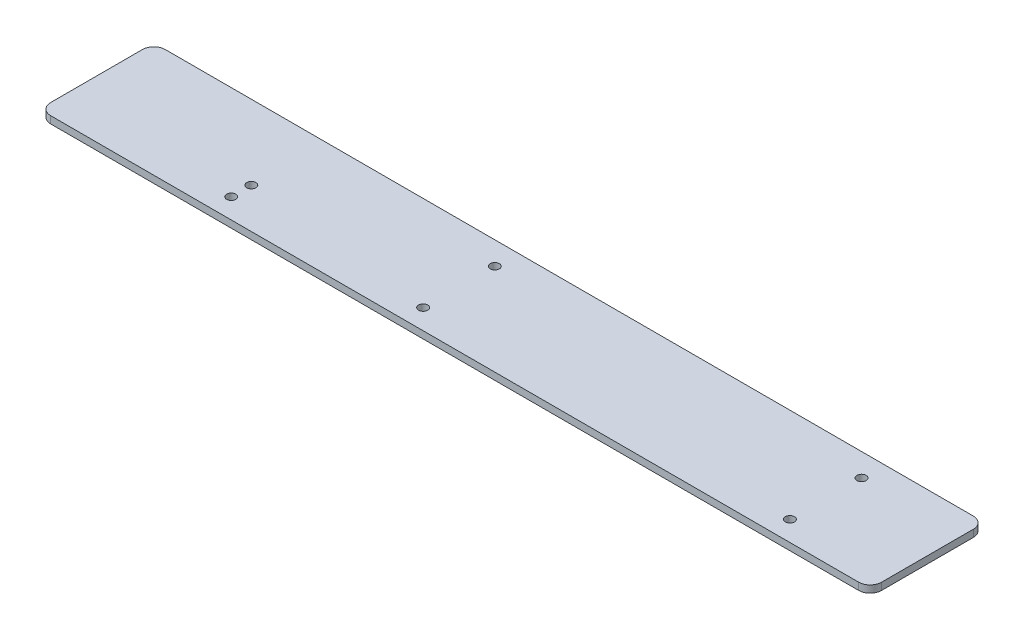
SolidWorks part; units mm, degrees
ref_plane "Front Plane" through (0, 0, 0) normal (0, 0, 1) x (1, 0, 0)
ref_plane "Top Plane" through (0, 0, 0) normal (0, 1, 0) x (1, 0, 0)
ref_plane "Right Plane" through (0, 0, 0) normal (1, 0, 0) x (0, 0, -1)
sketch "Sketch1" plane through (0, 0, 0) normal (0, 1, 0) x (1, 0, 0)
  line L0 (-184.15, -16.51) -> (184.15, -16.51) construction
  line L1 (-184.15, 25.4) -> (184.15, 25.4)
  line L2 (-184.15, 25.4) -> (-184.15, -25.4)
  line L3 (-184.15, -25.4) -> (184.15, -25.4)
  line L4 (184.15, 25.4) -> (184.15, -25.4)
  line L5 (-184.15, 25.4) -> (184.15, -25.4) construction
  line L6 (-184.15, -25.4) -> (184.15, 25.4) construction
  line L7 (-22.86, -16.51) -> (-22.86, 15.24) construction
  line L8 (139.7, -16.51) -> (139.7, 15.24) construction
  line L9 (-107.95, -16.51) -> (-107.95, -7.62) construction
  circle A0 centre (139.7, 15.24) radius 2.032
  circle A1 centre (139.7, -16.51) radius 2.032
  circle A2 centre (-22.86, 15.24) radius 2.032
  circle A3 centre (-22.86, -16.51) radius 2.032
  circle A4 centre (-107.95, -16.51) radius 2.032
  circle A5 centre (-107.95, -7.62) radius 2.032
  point P0 (0, 0)
  dimension "D4" = 4.064
  dimension "D8" = 8.89
  dimension "D1" = 50.8
  dimension "D2" = 368.3
  dimension "D3" = 8.89
  dimension "D5" = 31.75
  dimension "D6" = 44.45
  dimension "D7" = 207.01
  dimension "D9" = 292.1
extrude "Boss-Extrude1" add sketch "Sketch1" along normal blind 3.175
fillet "Fillet1" radius 5.08 4 edges at (184.15, 1.5875, 25.4) (184.15, 1.5875, -25.4) (-184.15, 1.5875, -25.4) (-184.15, 1.5875, 25.4)
